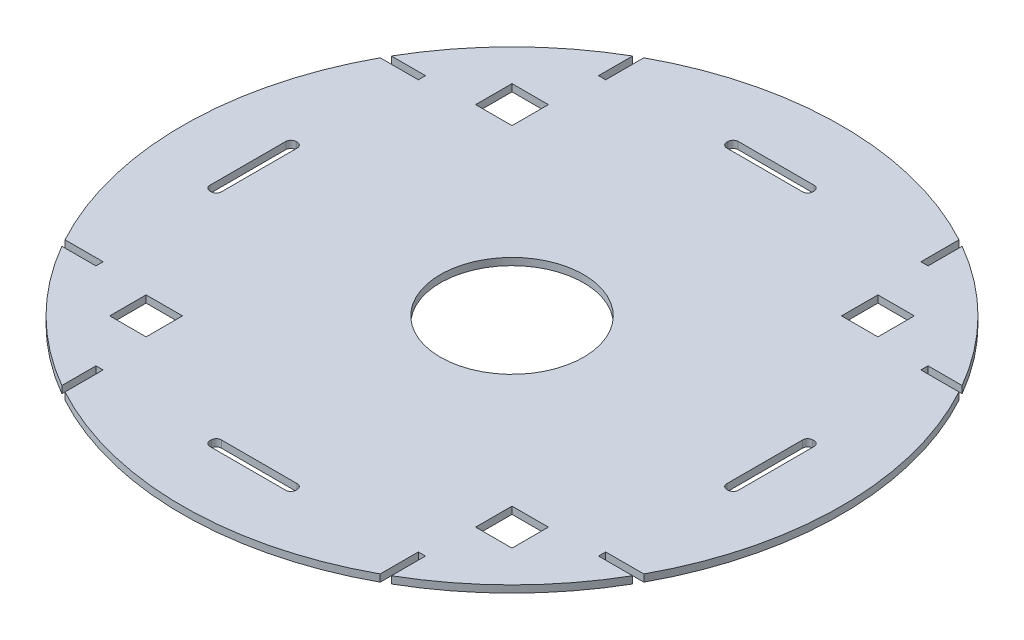
SolidWorks part; units mm, degrees
ref_plane "Front Plane" through (0, 0, 0) normal (0, 0, 1) x (1, 0, 0)
ref_plane "Top Plane" through (0, 0, 0) normal (0, 1, 0) x (1, 0, 0)
ref_plane "Right Plane" through (0, 0, 0) normal (1, 0, 0) x (0, 0, -1)
sketch "Sketch1" plane through (0, 0, 0) normal (0, 1, 0) x (1, 0, 0)
  line L0 (140.4, 140.4) -> (140.4, 115)
  line L1 (-140.4, 140.4) -> (140.4, 140.4) construction
  line L2 (-140.4, 140.4) -> (-140.4, -140.4) construction
  line L3 (-140.4, -140.4) -> (140.4, -140.4) construction
  line L4 (140.4, 140.4) -> (140.4, -140.4) construction
  line L5 (0, -140.4) -> (0, 140.4) construction
  line L6 (-140.4, 0) -> (140.4, 0) construction
  line L7 (-140.4, 140.4) -> (-115, 140.4)
  line L8 (-140.4, 140.4) -> (-140.4, 115)
  line L9 (-140.4, 115) -> (-115, 115)
  line L10 (-115, 140.4) -> (-115, 115)
  line L11 (140.4, 140.4) -> (115, 140.4)
  line L12 (115, 140.4) -> (115, 115)
  line L13 (140.4, 115) -> (115, 115)
  line L14 (140.4, -140.4) -> (115, -140.4)
  line L15 (140.4, -140.4) -> (140.4, -115)
  line L16 (115, -140.4) -> (115, -115)
  line L17 (140.4, -115) -> (115, -115)
  line L18 (-115, -140.4) -> (-115, -115)
  line L19 (-140.4, -140.4) -> (-115, -140.4)
  line L20 (-140.4, -140.4) -> (-140.4, -115)
  line L21 (-140.4, -115) -> (-115, -115)
  line L22 (175.4, 110) -> (201.9901, 110)
  line L23 (-115, 175.4) -> (-110, 175.4)
  line L24 (-115, 175.4) -> (-115, 199.1858)
  line L25 (175.4, 115) -> (175.4, 110)
  line L26 (-110, 175.4) -> (-110, 201.9901)
  line L27 (-175.4, 115) -> (-199.1858, 115)
  line L28 (-175.4, 115) -> (-175.4, 110)
  line L29 (-175.4, 110) -> (-201.9901, 110)
  line L30 (175.4, 115) -> (199.1858, 115)
  line L31 (110, 175.4) -> (110, 201.9901)
  line L32 (115, 175.4) -> (110, 175.4)
  line L33 (115, 175.4) -> (115, 199.1858)
  line L34 (175.4, -110) -> (201.9901, -110)
  line L35 (175.4, -115) -> (175.4, -110)
  line L36 (175.4, -115) -> (199.1858, -115)
  line L37 (115, -175.4) -> (110, -175.4)
  line L38 (115, -175.4) -> (115, -199.1858)
  line L39 (110, -175.4) -> (110, -201.9901)
  line L40 (-115, -175.4) -> (-115, -199.1858)
  line L41 (-115, -175.4) -> (-110, -175.4)
  line L42 (-110, -175.4) -> (-110, -201.9901)
  line L43 (-175.4, -110) -> (-201.9901, -110)
  line L44 (-175.4, -115) -> (-175.4, -110)
  line L45 (-175.4, -115) -> (-199.1858, -115)
  line L46 (184.4, 26.5) -> (184.4, -26.5)
  line L47 (-26.5, 184.4) -> (26.5, 184.4)
  line L48 (-30, 180.9) -> (-30, 179.9)
  line L49 (-26.5, 176.4) -> (26.5, 176.4)
  line L50 (30, 180.9) -> (30, 179.9)
  line L51 (0, 176.4) -> (0, 184.4) construction
  line L52 (-30, 180.4) -> (30, 180.4) construction
  line L53 (180.9, 30) -> (179.9, 30)
  line L54 (176.4, 26.5) -> (176.4, -26.5)
  line L55 (180.9, -30) -> (179.9, -30)
  line L56 (176.4, 0) -> (184.4, 0) construction
  line L57 (180.4, 30) -> (180.4, -30) construction
  line L58 (26.5, -184.4) -> (-26.5, -184.4)
  line L59 (30, -180.9) -> (30, -179.9)
  line L60 (26.5, -176.4) -> (-26.5, -176.4)
  line L61 (-30, -180.9) -> (-30, -179.9)
  line L62 (0, -176.4) -> (0, -184.4) construction
  line L63 (30, -180.4) -> (-30, -180.4) construction
  line L64 (-184.4, -26.5) -> (-184.4, 26.5)
  line L65 (-180.9, -30) -> (-179.9, -30)
  line L66 (-176.4, -26.5) -> (-176.4, 26.5)
  line L67 (-180.9, 30) -> (-179.9, 30)
  line L68 (-176.4, 0) -> (-184.4, 0) construction
  line L69 (-180.4, -30) -> (-180.4, 30) construction
  arc A0 (-115, 199.1858) -> (-199.1858, 115) centre (0, 0) ccw
  circle A1 centre (0, 0) radius 50
  arc A2 (-201.9901, 110) -> (-201.9901, -110) centre (0, 0) ccw
  arc A3 (110, 201.9901) -> (-110, 201.9901) centre (0, 0) ccw
  arc A4 (199.1858, 115) -> (115, 199.1858) centre (0, 0) ccw
  arc A5 (201.9901, -110) -> (201.9901, 110) centre (0, 0) ccw
  arc A6 (115, -199.1858) -> (199.1858, -115) centre (0, 0) ccw
  arc A7 (-110, -201.9901) -> (110, -201.9901) centre (0, 0) ccw
  arc A8 (-199.1858, -115) -> (-115, -199.1858) centre (0, 0) ccw
  arc A9 (26.5, 184.4) -> (30, 180.9) centre (26.5, 180.9) cw
  arc A10 (-26.5, 184.4) -> (-30, 180.9) centre (-26.5, 180.9) ccw
  arc A11 (26.5, 176.4) -> (30, 179.9) centre (26.5, 179.9) ccw
  arc A12 (-30, 179.9) -> (-26.5, 176.4) centre (-26.5, 179.9) ccw
  arc A13 (184.4, -26.5) -> (180.9, -30) centre (180.9, -26.5) cw
  arc A14 (184.4, 26.5) -> (180.9, 30) centre (180.9, 26.5) ccw
  arc A15 (176.4, -26.5) -> (179.9, -30) centre (179.9, -26.5) ccw
  arc A16 (179.9, 30) -> (176.4, 26.5) centre (179.9, 26.5) ccw
  arc A17 (-26.5, -184.4) -> (-30, -180.9) centre (-26.5, -180.9) cw
  arc A18 (26.5, -184.4) -> (30, -180.9) centre (26.5, -180.9) ccw
  arc A19 (-26.5, -176.4) -> (-30, -179.9) centre (-26.5, -179.9) ccw
  arc A20 (30, -179.9) -> (26.5, -176.4) centre (26.5, -179.9) ccw
  arc A21 (-184.4, 26.5) -> (-180.9, 30) centre (-180.9, 26.5) cw
  arc A22 (-184.4, -26.5) -> (-180.9, -30) centre (-180.9, -26.5) ccw
  arc A23 (-176.4, 26.5) -> (-179.9, 30) centre (-179.9, 26.5) ccw
  arc A24 (-179.9, -30) -> (-176.4, -26.5) centre (-179.9, -26.5) ccw
  point P55 (0, 180.4)
  point P61 (30, 184.4)
  point P65 (-30, 184.4)
  point P68 (30, 176.4)
  point P71 (0, 0)
  point P74 (180.4, 0)
  point P91 (0, -180.4)
  point P108 (-180.4, 0)
  point P125 (0, 0)
  dimension "D1" = 460
  dimension "D4" = 100
  dimension "D12" = 3.5
  dimension "D2" = 280.8
  dimension "D3" = 25.4
  dimension "D5" = 5
  dimension "D6" = 5
  dimension "D7" = 35
  dimension "D8" = 35
  dimension "D9" = 60
  dimension "D10" = 8
  dimension "D11" = 40
  dimension "D13" = 4
extrude "Boss-Extrude1" add sketch "Sketch1" along normal blind 5
